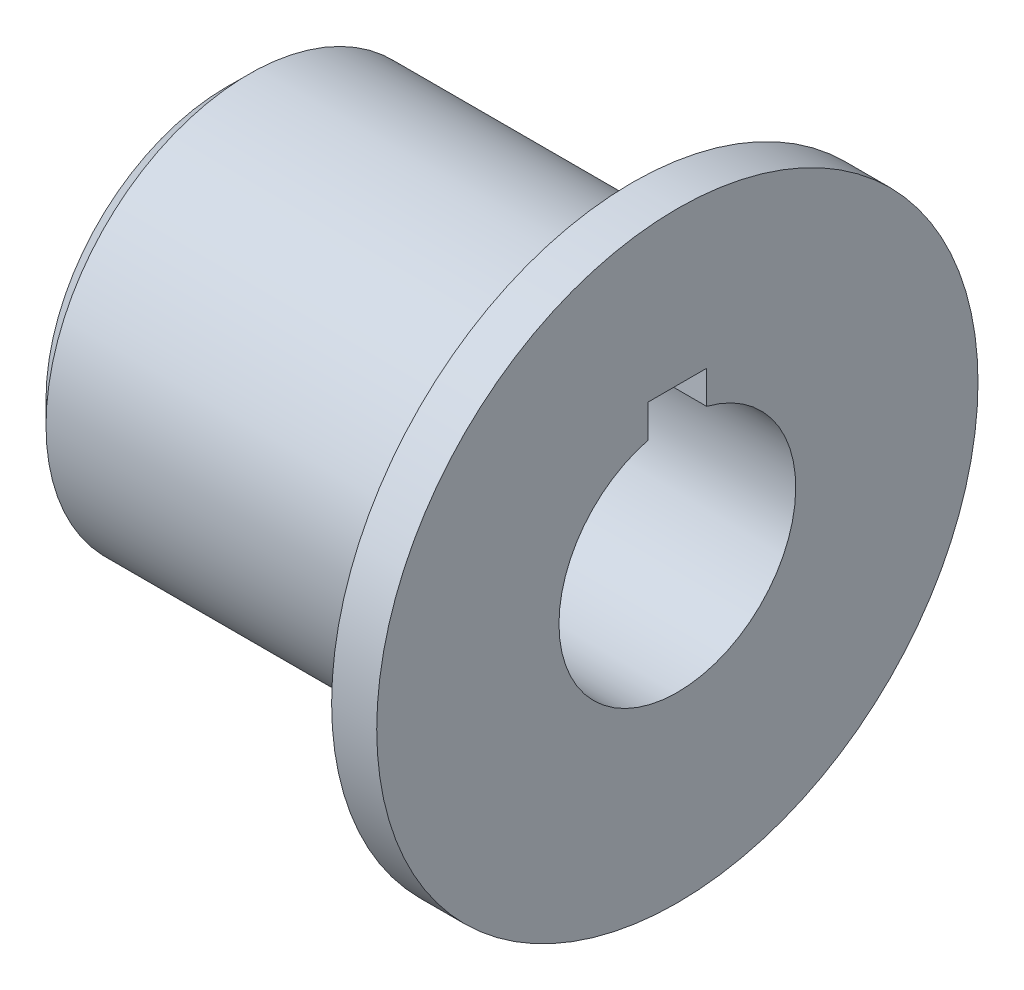
SolidWorks part; units mm, degrees
material "1060 Alloy"
ref_plane "Front Plane" through (0, 0, 0) normal (0, 0, 1) x (1, 0, 0)
ref_plane "Top Plane" through (0, 0, 0) normal (0, 1, 0) x (1, 0, 0)
ref_plane "Right Plane" through (0, 0, 0) normal (1, 0, 0) x (0, 0, -1)
sketch "Sketch1" plane through (0, 0, 0) normal (0, 0, 1) x (1, 0, 0)
  line L0 (0, 0) -> (59.2732, 0) construction
  line L1 (0, 0) -> (0, 6.858)
  line L2 (0, 6.858) -> (13.716, 6.858)
  line L3 (13.716, 6.858) -> (13.716, 10.16)
  line L4 (13.716, 10.16) -> (15.24, 10.16)
  line L5 (15.24, 10.16) -> (15.24, 4.0005)
  line L6 (15.24, 4.0005) -> (9.525, 4.0005)
  line L7 (9.525, 4.0005) -> (9.525, 0)
  line L8 (0, 0) -> (9.525, 0)
  dimension "D1" = 8.001
  dimension "D2" = 5.715
  dimension "D3" = 1.524
  dimension "D4" = 15.24
  dimension "D5" = 13.716
  dimension "D6" = 20.32
revolve "Revolve1" add sketch "Sketch1" angle 360 about L0
cosmetic thread "Cosmetic Thread1" parameters "D1"=5.08, "D2"=12.7
chamfer "Chamfer1" distance 0.762 angle 45 1 edges at (0, 0, 6.858)
sketch "Sketch3" plane through (0, 0, 0) normal (0, 0, 1) x (1, 0, 0)
  line L0 (15.24, 4.9911) -> (11.5192, 4.9911)
  line L1 (15.24, 4.9911) -> (15.24, 3.8227)
  line L2 (15.24, 3.8227) -> (9.525, 3.8227)
  line L4 (15.24, -10.16) -> (15.24, 10.16) construction
  line L5 (9.525, -4.0005) -> (9.525, 4.0005) construction
  arc A0 (11.5192, 4.9911) -> (9.525, 3.8227) centre (11.5192, 2.7051) ccw
  dimension "D2" = 2.286
  dimension "D1" = 4.9911
  dimension "D3" = 1.1684
extrude "Extrude1" cut sketch "Sketch3" against normal mid plane 1.9812
